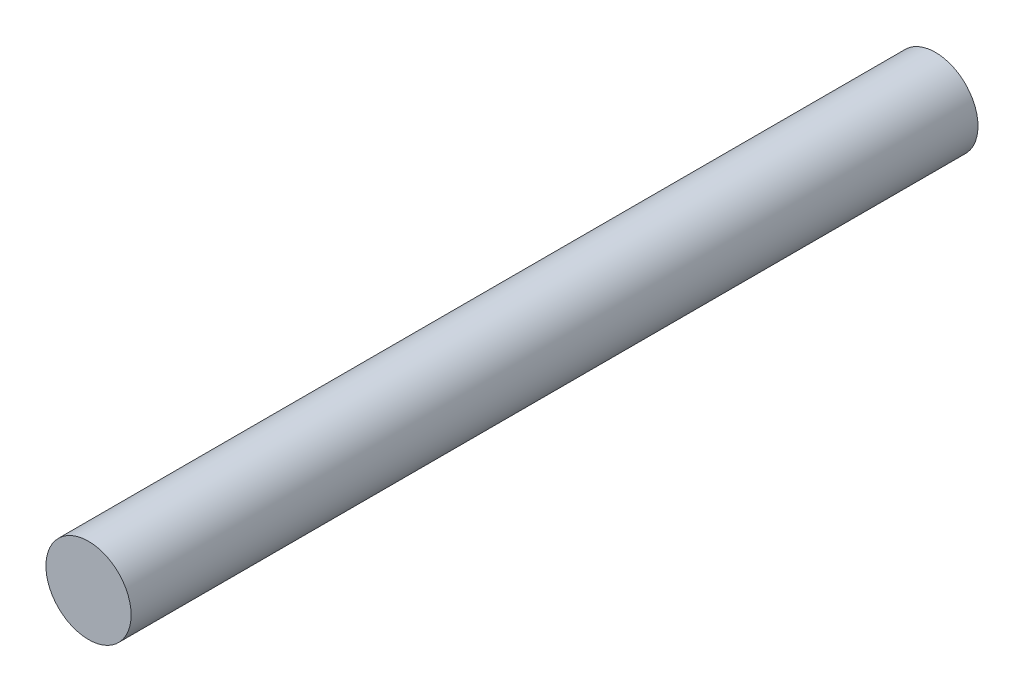
SolidWorks part; units mm, degrees
ref_plane "Front Plane" through (0, 0, 0) normal (0, 0, 1) x (1, 0, 0)
ref_plane "Top Plane" through (0, 0, 0) normal (0, 1, 0) x (1, 0, 0)
ref_plane "Right Plane" through (0, 0, 0) normal (1, 0, 0) x (0, 0, -1)
sketch "Sketch1" plane through (0, 0, 0) normal (0, 0, 1) x (1, 0, 0)
  circle A0 centre (0, 0) radius 3.175
  dimension "D1" = 6.35
extrude "Boss-Extrude1" add sketch "Sketch1" along normal blind 63.1346
